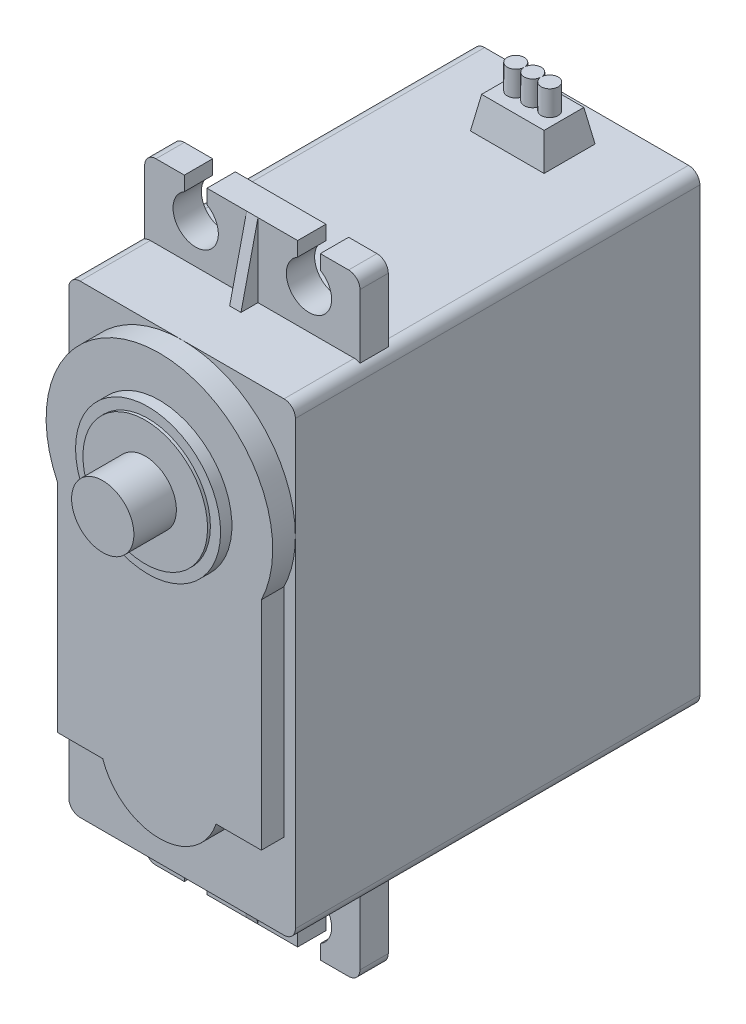
SolidWorks part; units mm, degrees
ref_plane "Plan de face" through (0, 0, 0) normal (0, 0, 1) x (1, 0, 0)
ref_plane "Plan de dessus" through (0, 0, 0) normal (0, 1, 0) x (1, 0, 0)
ref_plane "Plan de droite" through (0, 0, 0) normal (1, 0, 0) x (0, 0, -1)
sketch "Esquisse1" plane through (0, 0, 0) normal (0, 0, 1) x (1, 0, 0)
  line L1 (0, 0) -> (20, 0)
  line L2 (0, 0) -> (0, 41)
  line L3 (0, 41) -> (20, 41)
  line L4 (20, 0) -> (20, 41)
  dimension "D1" = 20
  dimension "D2" = 41
extrude "Boss.-Extru.1" add sketch "Esquisse1" along normal blind 37.7
fillet "Congé1" radius 1 4 edges at (20, 0, 18.85) (0, 0, 18.85) (20, 41, 18.85) (0, 41, 18.85)
sketch "Esquisse2" plane through (0, 0, 0) normal (0, -1, 0) x (1, 0, 0)
  line L1 (0.5, 29.5) -> (19.5, 29.5)
  line L2 (0.5, 29.5) -> (0.5, 27)
  line L3 (0.5, 27) -> (19.5, 27)
  line L4 (19.5, 29.5) -> (19.5, 27)
  line L6 (1, 0) -> (19, 0) construction
  line L7 (10, 37.7) -> (10, 0) construction
  line L8 (1, 37.7) -> (19, 37.7) construction
  line L9 (1, 0) -> (19, 0) construction
  dimension "D1" = 27
  dimension "D2" = 2.5
  dimension "D3" = 19
extrude "Boss.-Extru.2" add sketch "Esquisse2" along normal blind 6.5 and the other way blind 47.5
sketch "Esquisse3" plane through (0, 0, 37.7) normal (0, 0, 1) x (1, 0, 0)
  line L1 (10, 31) -> (10, 7.4675) construction
  line L2 (0, 40) -> (0, 1) construction
  line L3 (20, 1) -> (20, 40) construction
  line L4 (19, 41) -> (1, 41) construction
  circle A0 centre (10, 31) radius 6.4
  dimension "D1" = 10
  dimension "D2" = 12.8
extrude "Boss.-Extru.3" add sketch "Esquisse3" along normal blind 1
sketch "Esquisse4" plane through (0, 0, 38.7) normal (0, 0, 1) x (1, 0, 0)
  circle A0 centre (10, 31) radius 2.75
extrude "Boss.-Extru.4" add sketch "Esquisse4" along normal blind 4
sketch "Esquisse5" plane through (0, 0, 29.5) normal (0, 0, 1) x (1, 0, 0)
  line L0 (-13.3203, 20.5) -> (35.5882, 20.5) construction
  line L1 (19.5, 47.5) -> (0.5, 47.5) construction
  line L2 (0.5, -6.5) -> (19.5, -6.5) construction
  line L3 (10, 5.7549) -> (10, -14.6664) construction
  line L4 (19.5, 0.134) -> (19.5, -6.5) construction
  line L5 (0.5, 0.134) -> (0.5, -6.5) construction
  line L8 (16, -7.5) -> (14, -7.5)
  line L9 (16, -7.5) -> (16, -5.2321)
  line L10 (19.5, -6.5) -> (0.5, -6.5) construction
  line L11 (14, -7.5) -> (14, -5.2321)
  line L12 (15, -7.5) -> (15, -3.5) construction
  line L13 (1, 0) -> (19, 0) construction
  line L14 (16, -7.5) -> (16, -5.2321)
  line L15 (14, -7.5) -> (14, -5.2321)
  line L16 (6, -7.5) -> (6, -5.2321)
  line L17 (4, -7.5) -> (6, -7.5)
  line L18 (4, -7.5) -> (4, -5.2321)
  line L19 (16, 48.5) -> (14, 48.5)
  line L20 (16, 48.5) -> (16, 46.2321)
  line L21 (14, 48.5) -> (14, 46.2321)
  line L22 (4, 48.5) -> (4, 46.2321)
  line L23 (4, 48.5) -> (6, 48.5)
  line L24 (6, 48.5) -> (6, 46.2321)
  arc A0 (4, -5.2321) -> (6, -5.2321) centre (5, -3.5) cw
  arc A1 (16, -5.2321) -> (14, -5.2321) centre (15, -3.5) ccw
  arc A2 (4, 46.2321) -> (6, 46.2321) centre (5, 44.5) ccw
  arc A3 (16, 46.2321) -> (14, 46.2321) centre (15, 44.5) cw
  line M3 (0.5, -6.5) -> (19.5, -6.5)
  dimension "D1" = 2
  dimension "D2" = 3.5
  dimension "D6" = 1
  dimension "D3" = 5
  dimension "D5" = 2
extrude "Enlèv. mat.-Extru.1" cut sketch "Esquisse5" against normal blind 4 contours A3 L20 L19 L21 | L22 A2 L24 L23 | A0 L18 L16 M3 | L9 A1 L11 M3
sketch "Esquisse6" plane through (0, 41, 0) normal (0, 1, 0) x (1, 0, 0)
  line L0 (10, 0) -> (10, -17.9681) construction
  line L1 (13.25, -7) -> (6.75, -7)
  line L2 (13.25, -7) -> (13.25, -2.5)
  line L3 (13.25, -2.5) -> (6.75, -2.5)
  line L4 (6.75, -7) -> (6.75, -2.5)
  line L5 (19, 0) -> (1, 0) construction
  dimension "D1" = 7
  dimension "D2" = 4.5
  dimension "D3" = 6.5
extrude "Boss.-Extru.6" add sketch "Esquisse6" along normal blind 2.8 draft 10
sketch "Esquisse7" plane through (0, 43.8, 0) normal (0, 1, 0) x (1, 0, 0)
  line L0 (12.7563, -4.75) -> (7.2437, -4.75) construction
  line L1 (12.7563, -6.5063) -> (12.7563, -2.9937) construction
  line L2 (7.2437, -2.9937) -> (7.2437, -6.5063) construction
  line L4 (10.7517, -4.8) -> (10.7483, -4.8)
  line L5 (10.7517, -4.7) -> (10.7483, -4.7)
  line L6 (9.2483, -4.7) -> (9.2517, -4.7)
  line L7 (9.2483, -4.8) -> (9.2517, -4.8)
  arc A0 (10.7483, -4.7) -> (9.2517, -4.7) centre (10, -4.75) ccw
  arc A1 (9.2483, -4.7) -> (9.2483, -4.8) centre (8.5, -4.75) ccw
  arc A2 (10.7517, -4.8) -> (10.7517, -4.7) centre (11.5, -4.75) ccw
  arc A3 (9.2517, -4.8) -> (10.7483, -4.8) centre (10, -4.75) ccw
  point P23 (10, -4.75)
  dimension "D1" = 1.5
  dimension "D2" = 0.05
  dimension "D3" = 2
extrude "Boss.-Extru.12" add sketch "Esquisse7" along normal blind 2.2
sketch3d "Esquisse3D1"
  line L0 (10, -6.5, 29.5) -> (10, 0, 29.5)
  line L1 (1, 0, 29.5) -> (19, 0, 29.5) construction
  line L2 (10, 0, 29.5) -> (10, 0, 31)
  line L3 (10, 0, 31) -> (10, -6.5, 29.5)
  line L4 (20, -6.5, 29.5) -> (0, -6.5, 29.5) construction
  line L5 (10, 47.5, 29.5) -> (10, 41, 29.5)
  line L7 (19, 41, 29.5) -> (1, 41, 29.5) construction
  line L8 (10, 41, 29.5) -> (10, 41, 31)
  line L9 (10, 41, 31) -> (10, 47.5, 29.5)
  line L10 (14, 47.5, 29.5) -> (6, 47.5, 29.5) construction
  dimension "D1" = 10
  dimension "D2" = 1.5
  dimension "D3" = 1.5
extrude "Boss.-Extru.13" add sketch "Esquisse3D1" along direction (1, 0, 0) on the side of the normal blind 0.5 and the other way blind 0.5
sketch "Esquisse8" plane through (0, 0, 37.7) normal (0, 0, 1) x (1, 0, 0)
  line L0 (1, 26.6411) -> (1, 7.5)
  line L1 (1, 7.5) -> (5, 7.5)
  line L2 (10, 31) -> (10, 5.8854) construction
  line L3 (15, 7.5) -> (19, 7.5)
  line L4 (19, 7.5) -> (19, 26.6411)
  line L5 (0, 40) -> (0, 1) construction
  line L6 (19, 41) -> (1, 41) construction
  line L8 (-6.1443, 45.0222) -> (28.689, 45.0222)
  line L9 (-6.1443, 45.0222) -> (-6.1443, -1.2568)
  line L10 (-6.1443, -1.2568) -> (28.689, -1.2568)
  line L11 (28.689, 45.0222) -> (28.689, -1.2568)
  arc A0 (19, 26.6411) -> (1, 26.6411) centre (10, 31) ccw
  arc A1 (5, 7.5) -> (15, 7.5) centre (10, 9.1676) ccw
  dimension "D1" = 18
  dimension "D3" = 21.8324
  dimension "D4" = 33.5
  dimension "D2" = 10
extrude "Enlèv. mat.-Extru.2" cut sketch "Esquisse8" against normal blind 2
fillet "Congé2" radius 1 4 edges at (19.5, 47.5, 28.25) (0.5, 47.5, 28.25) (19.5, -6.5, 28.25) (0.5, -6.5, 28.25)
sketch "Esquisse9" plane through (0, 0, 38.7) normal (0, 0, 1) x (1, 0, 0)
  circle A0 centre (10, 31) radius 5.5
  dimension "D1" = 11
extrude "Boss.-Extru.14" add sketch "Esquisse9" along normal blind 0.25
